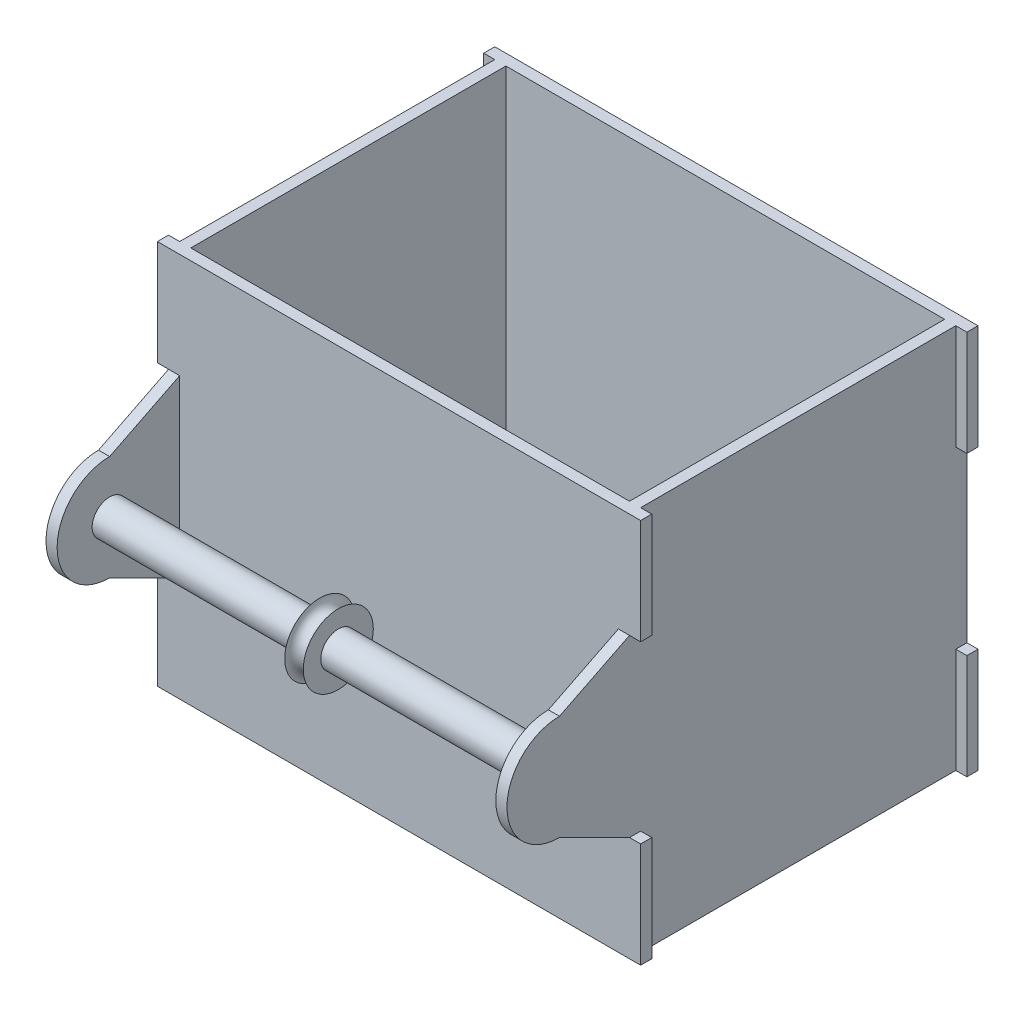
SolidWorks part; units mm, degrees
ref_plane "Front Plane" through (0, 0, 0) normal (0, 0, 1) x (1, 0, 0)
ref_plane "Top Plane" through (0, 0, 0) normal (0, 1, 0) x (1, 0, 0)
ref_plane "Right Plane" through (0, 0, 0) normal (1, 0, 0) x (0, 0, -1)
sketch "Sketch2" plane through (0, 0, 0) normal (0, 0, 1) x (1, 0, 0)
  line L0 (0, 50) -> (-3.175, 50)
  line L1 (131.65, 50) -> (0, 50) construction
  line L2 (131.65, 50) -> (131.65, 0)
  line L3 (131.65, 0) -> (0, 0) construction
  line L4 (0, 50) -> (0, 0)
  line L5 (-3.175, 50) -> (-3.175, 80)
  line L6 (-3.175, 80) -> (134.825, 80)
  line L7 (134.825, 80) -> (134.825, 50)
  line L8 (134.825, 50) -> (131.65, 50)
  line L9 (0, 0) -> (-3.175, 0)
  line L10 (-3.175, 0) -> (-3.175, -30)
  line L11 (-3.175, -30) -> (134.825, -30)
  line L12 (134.825, -30) -> (134.825, 0)
  line L13 (134.825, 0) -> (131.65, 0)
  dimension "D1" = 50
  dimension "D2" = 131.65
  dimension "D3" = 3.175
  dimension "D4" = 30
extrude "Boss-Extrude1" add sketch "Sketch2" along normal blind 3.175
sketch "Sketch3" plane through (0, 0, 3.175) normal (0, 0, 1) x (1, 0, 0)
  line L0 (-3.175, -30) -> (134.825, -30) construction
  line L1 (0, -30) -> (3.175, -30)
  line L2 (0, -30) -> (0, 80)
  line L3 (0, 80) -> (3.175, 80)
  line L4 (3.175, -30) -> (3.175, 80)
  line L5 (134.825, 80) -> (-3.175, 80) construction
  line L6 (131.65, 0) -> (131.65, 50) construction
  line L7 (131.65, -30) -> (128.475, -30)
  line L8 (131.65, -30) -> (131.65, 80)
  line L9 (131.65, 80) -> (128.475, 80)
  line L10 (128.475, -30) -> (128.475, 80)
  dimension "D1" = 3.175
  dimension "D2" = 3.175
extrude "Boss-Extrude2" add sketch "Sketch3" along normal blind 90
sketch "Sketch4" plane through (0, 0, 93.175) normal (0, 0, 1) x (1, 0, 0)
  line L0 (131.65, 50) -> (134.825, 50)
  line L1 (134.825, 50) -> (134.825, 80)
  line L2 (134.825, 80) -> (-3.175, 80)
  line L3 (-3.175, 80) -> (-3.175, 50)
  line L4 (-3.175, 50) -> (-1.5875, 50)
  line L5 (-3.175, 50) -> (0, 50) construction
  line L6 (-1.5875, 50) -> (0, 50)
  line L7 (0, 50) -> (0, 0)
  line L8 (0, 0) -> (-3.175, 0)
  line L9 (-3.175, 0) -> (-3.175, -30)
  line L10 (-3.175, -30) -> (134.825, -30)
  line L11 (134.825, -30) -> (134.825, 0)
  line L12 (134.825, 0) -> (131.65, 0)
  line L13 (131.65, -30) -> (131.65, 80) construction
  line L14 (131.65, 0) -> (131.65, 50)
extrude "Boss-Extrude3" add sketch "Sketch4" along normal blind 3.175
sketch "Sketch5" plane through (0, 0, 0) normal (-1, 0, 0) x (0, 0, 1)
  line L0 (96.35, 50) -> (96.35, 0)
  line L2 (116.35, 40) -> (96.35, 50)
  line L3 (116.35, 10) -> (96.35, 0)
  arc A0 (116.35, 10) -> (116.35, 40) centre (116.35, 25) ccw
extrude "Boss-Extrude4" add sketch "Sketch5" against normal blind 3.175
sketch "Sketch6" plane through (131.65, 0, 0) normal (1, 0, 0) x (0, 0, -1)
  line L0 (-96.35, 25) -> (-116.35, 25) construction
  line L1 (-96.35, 0) -> (-96.35, 50) construction
  line L2 (-96.35, 0) -> (-116.35, 10)
  line L3 (-116.35, 40) -> (-96.35, 50)
  line L4 (-96.35, 0) -> (-96.35, 50)
  arc A0 (-116.35, 40) -> (-116.35, 10) centre (-116.35, 25) ccw
extrude "Boss-Extrude5" add sketch "Sketch6" against normal blind 3.175
sketch "Sketch7" plane through (131.65, 0, 0) normal (1, 0, 0) x (0, 0, -1)
  circle A0 centre (-116.35, 25) radius 5
extrude "Boss-Extrude6" add sketch "Sketch7" against normal up to surface (128.475 mm away) up to face at (3.175, 25, 110.1)
ref_plane "Plane1" through (68.475, 0, 0) normal (-1, 0, 0) x (0, 0, 1)
sketch "Sketch8" plane through (68.475, 0, 0) normal (-1, 0, 0) x (0, 0, 1)
  line L0 (116.35, 40) -> (116.35, 10) construction
  circle A0 centre (116.35, 25) radius 10
extrude "Boss-Extrude7" add sketch "Sketch8" along normal blind 5.3
ref_plane "Plane2" through (0, 25, 0) normal (0, 1, 0) x (1, 0, 0)
sketch "Sketch10" plane through (0, 25, 0) normal (0, 1, 0) x (1, 0, 0)
  line L0 (68.475, -106.35) -> (63.175, -106.35) construction
  line L1 (63.175, -116.35) -> (43.5801, -116.35) construction
  line L2 (63.175, -111.35) -> (63.175, -121.35) construction
  circle A0 centre (65.825, -106.35) radius 2.65
revolve "Cut-Revolve1" cut sketch "Sketch10" angle 360 about L1
